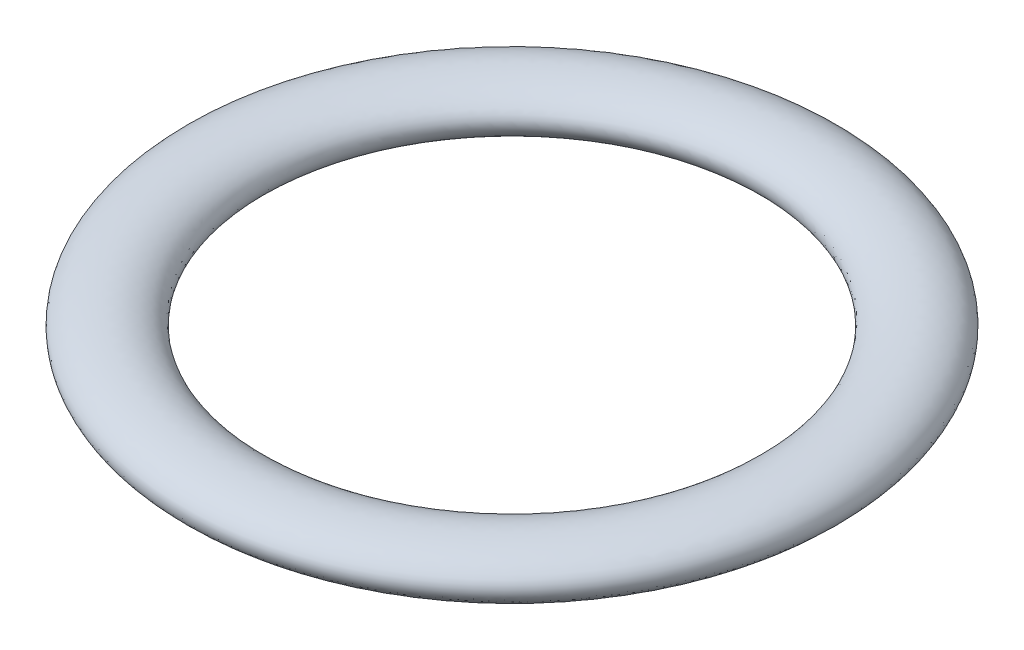
SolidWorks part; units mm, degrees
ref_plane "Front Plane" through (0, 0, 0) normal (0, 0, 1) x (1, 0, 0)
ref_plane "Top Plane" through (0, 0, 0) normal (0, 1, 0) x (1, 0, 0)
ref_plane "Right Plane" through (0, 0, 0) normal (1, 0, 0) x (0, 0, -1)
sketch "Reconstructed nominal axial profile" plane through (0, 0, 0) normal (0, 0, 1) x (1, 0, 0)
  line L0 (0, -500) -> (0, 50) construction
  ellipse E0 centre (8.675, 0) end of major axis (9.9867, 0) minor radius 0.725
revolve "Native revolved geometry" add sketch "Reconstructed nominal axial profile" angle 360 about L0
